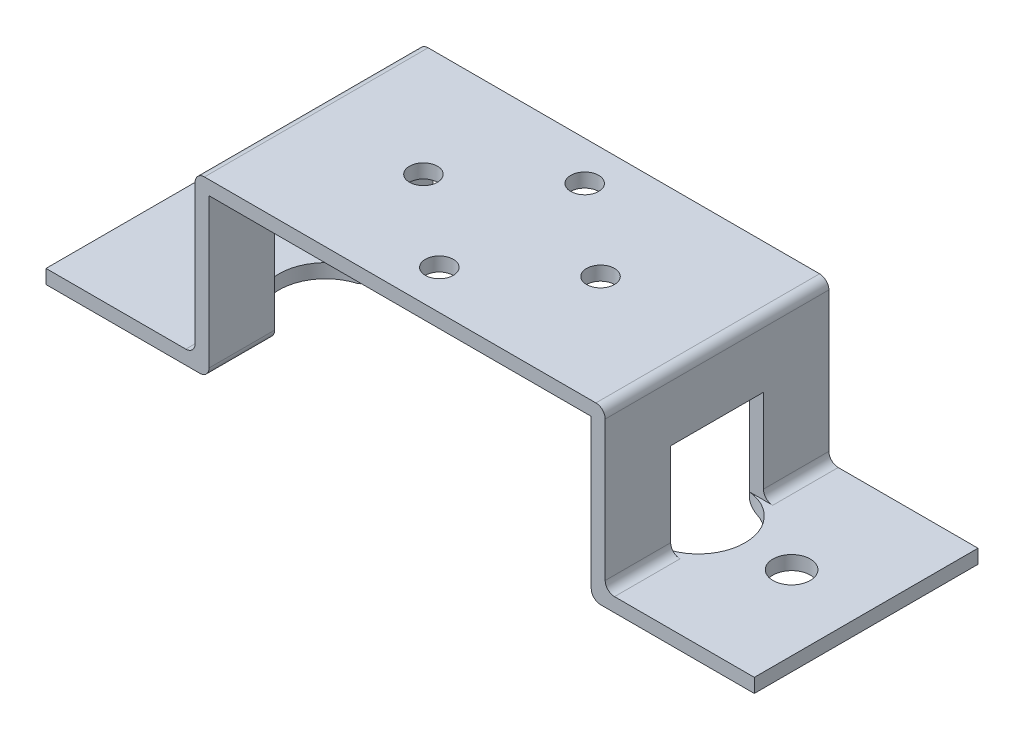
SolidWorks part; units mm, degrees
ref_plane "Front Plane" through (0, 0, 0) normal (0, 0, 1) x (1, 0, 0)
ref_plane "Top Plane" through (0, 0, 0) normal (0, 1, 0) x (1, 0, 0)
ref_plane "Right Plane" through (0, 0, 0) normal (1, 0, 0) x (0, 0, -1)
sketch3d "3DSketch1"
  line L0 (0, 0, 0) -> (17.5, 0, 0)
  line L1 (17.5, 0, 0) -> (17.5, 17, 0)
  line L2 (17.5, 17, 0) -> (58.5, 17, 0)
  line L3 (58.5, 17, 0) -> (58.5, 0, 0)
  line L4 (58.5, 0, 0) -> (76, 0, 0)
  line L5 (76, 0, 0) -> (76, 1.5, 0)
  line L6 (76, 1.5, 0) -> (60, 1.5, 0)
  line L7 (60, 1.5, 0) -> (60, 18.5, 0)
  line L8 (60, 18.5, 0) -> (16, 18.5, 0)
  line L9 (16, 18.5, 0) -> (16, 1.5, 0)
  line L10 (16, 1.5, 0) -> (0, 1.5, 0)
  line L11 (0, 1.5, 0) -> (0, 0, 0)
  dimension "D1" = 1.5
  dimension "D2" = 17
  dimension "D3" = 41
  dimension "D5" = 1.5
  dimension "D7" = 17
  dimension "D8" = 44
  dimension "D9" = 16
extrude "Boss-Extrude2" add sketch "3DSketch1" along direction (0, 0, 1) on the side of the normal blind 24 contours L0 L1 L2 L3 L4 L5 L6 L7 L8 L9 L10 L11
sketch "Sketch12" plane through (0, 1.5, 0) normal (0, 1, 0) x (1, 0, 0)
  line L0 (0, -12) -> (76, -12) construction
  line L1 (76, 0) -> (76, -24) construction
  line L2 (0, 0) -> (0, -24) construction
  point P2 (79.5, -20.5)
  point P5 (0, -20.5)
sketch "Sketch17" plane through (0, 1.5, 0) normal (0, 1, 0) x (1, 0, 0)
  line L0 (0, -12) -> (76, -12) construction
  line L1 (68, -12) -> (76, -12) construction
  line L2 (76, 0) -> (76, -24) construction
  line L3 (8, -12) -> (0, -12) construction
  line L4 (0, 0) -> (0, -24) construction
  circle A0 centre (8, -12) radius 2
  circle A1 centre (68, -12) radius 2
  point P9 (0, -15)
  dimension "D3" = 4
  dimension "D1" = 60
extrude "Cut-Extrude1" cut sketch "Sketch17" against normal through all both and the other way through all
sketch "Sketch18" plane through (0, 18.5, 0) normal (0, 1, 0) x (1, 0, 0)
  line L0 (16, -12) -> (60, -12) construction
  line L1 (16, 0) -> (16, -24) construction
  line L2 (60, 0) -> (60, -24) construction
  line L3 (38, -12) -> (38, -24) construction
  line L4 (38, -24) -> (38, 0) construction
  line L5 (60, -24) -> (16, -24) construction
  line L6 (60, 0) -> (16, 0) construction
  point P8 (39, -41)
  point P12 (39, 0)
hole_wizard "Ø3.0mm Dowel Hole1" positions "Sketch20" profile "Sketch21" hole size "Ø3.0" standard "ANSI Metric" end condition through all
sketch "Sketch20" plane through (0, 18.5, 0) normal (0, 1, 0) x (1, 0, 0)
  line L0 (0, -12) -> (76, -12) construction
  line L1 (38, 0) -> (38, -24) construction
  line L2 (16, -12) -> (60, -12) construction
  point P0 (28.5, -12)
  point P11 (47.5, -12)
  point P12 (38, -19.8)
  point P21 (38, -4.2)
  dimension "D1" = 19
  dimension "D2" = 15.6
sketch "Sketch21" plane through (28.5, 18.5, 12) normal (1, 0, 0) x (0, 0, 1)
  line L0 (0, 0) -> (0, 18.5001)
  line L1 (0, 18.5001) -> (1.5, 18.5001)
  line L2 (1.5, 18.5001) -> (1.5, 0)
  line L5 (1.5, 0) -> (0, 0)
  line L11 (0, -6.35) -> (0, 107.95) construction
  dimension "Thru Hole Dia." = 3
  dimension "Thru Hole Depth" = 18.5001
sketch "Sketch22" plane through (0, 1.5, 0) normal (0, 1, 0) x (1, 0, 0)
  line L0 (38, 0) -> (38, -24) construction
  circle A0 centre (18, -12) radius 5
  circle A1 centre (58, -12) radius 5
  dimension "D1" = 10
extrude "Cut-Extrude2" cut sketch "Sketch22" against normal up to surface (1.5 mm away) up to face at (8, 0, 10)
sketch "Sketch23" plane through (16, 0, 0) normal (-1, 0, 0) x (0, 0, 1)
  line L0 (16.9749, 1.5) -> (16.9749, 0) construction
  line L1 (7.0251, 1.5) -> (16.9749, 1.5)
  line L2 (7.0251, 1.5) -> (7.0251, 11.5)
  line L3 (7.0251, 11.5) -> (16.9749, 11.5)
  line L4 (16.9749, 1.5) -> (16.9749, 11.5)
  dimension "D1" = 10
extrude "Cut-Extrude3" cut sketch "Sketch23" against normal through all both and the other way through all
fillet "Fillet1" radius 1 10 edges
